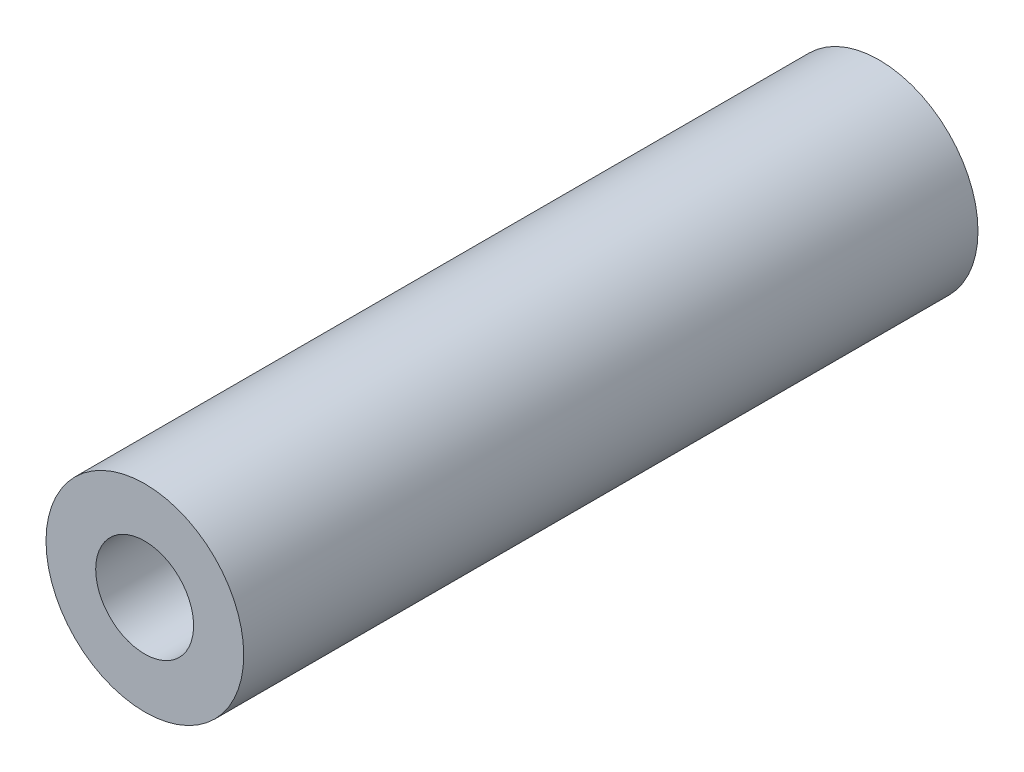
SolidWorks part; units mm, degrees
ref_plane "Plan de face" through (0, 0, 0) normal (0, 0, 1) x (1, 0, 0)
ref_plane "Plan de dessus" through (0, 0, 0) normal (0, 1, 0) x (1, 0, 0)
ref_plane "Plan de droite" through (0, 0, 0) normal (1, 0, 0) x (0, 0, -1)
sketch "Esquisse1" plane through (0, 0, 0) normal (0, 0, 1) x (1, 0, 0)
  circle A0 centre (-0.1094, 0.0577) radius 6.0592
  circle A1 centre (-0.123, 0.0761) radius 3
extrude "Boss.-Extru.1" add sketch "Esquisse1" along normal blind 45
